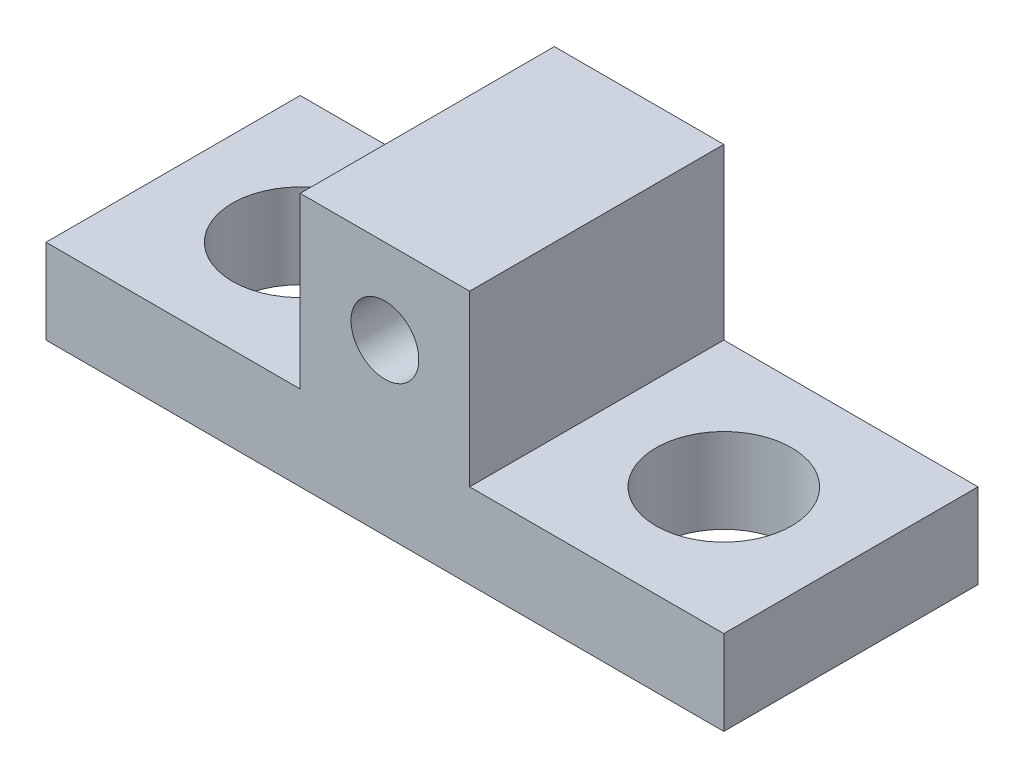
SolidWorks part; units mm, degrees
ref_plane "前视基准面" through (0, 0, 0) normal (0, 0, 1) x (1, 0, 0)
ref_plane "上视基准面" through (0, 0, 0) normal (0, 1, 0) x (1, 0, 0)
ref_plane "右视基准面" through (0, 0, 0) normal (1, 0, 0) x (0, 0, -1)
other "Configuration Table"
sketch "草图1" plane through (0, 0, 0) normal (0, 1, 0) x (1, 0, 0)
  line L1 (-20, 7.5) -> (20, 7.5)
  line L2 (-20, 7.5) -> (-20, -7.5)
  line L3 (-20, -7.5) -> (20, -7.5)
  line L4 (20, 7.5) -> (20, -7.5)
  line L5 (-20, 7.5) -> (20, -7.5) construction
  line L6 (-20, -7.5) -> (20, 7.5) construction
  point P0 (0, 0)
  dimension "D1" = 40
  dimension "D2" = 15
extrude "凸台-拉伸3" add sketch "草图1" along normal blind 5
sketch "草图2" plane through (0, 5, 0) normal (0, 1, 0) x (1, 0, 0)
  line L0 (-20, -7.5) -> (20, -7.5) construction
  line L1 (-5, 7.5) -> (5, 7.5)
  line L2 (-5, 7.5) -> (-5, -7.5)
  line L3 (-5, -7.5) -> (5, -7.5)
  line L4 (5, 7.5) -> (5, -7.5)
  line L5 (-5, 7.5) -> (5, -7.5) construction
  line L6 (-5, -7.5) -> (5, 7.5) construction
  point P0 (0, 0)
  dimension "D1" = 10
extrude "凸台-拉伸4" add sketch "草图2" along normal blind 10
sketch "草图4" plane through (0, 0, -7.5) normal (0, 0, -1) x (-1, 0, 0)
  circle A0 centre (0, 10) radius 2
extrude "切除-拉伸1" cut sketch "草图4" against normal through all
sketch "草图8" plane through (0, 5, 0) normal (0, 1, 0) x (1, 0, 0)
  circle A0 centre (-12.5, 0) radius 4
extrude "切除-拉伸3" cut sketch "草图8" against normal through all
mirror "镜向1" about plane through (0, 0, 0) normal (1, 0, 0) of "切除-拉伸3"
